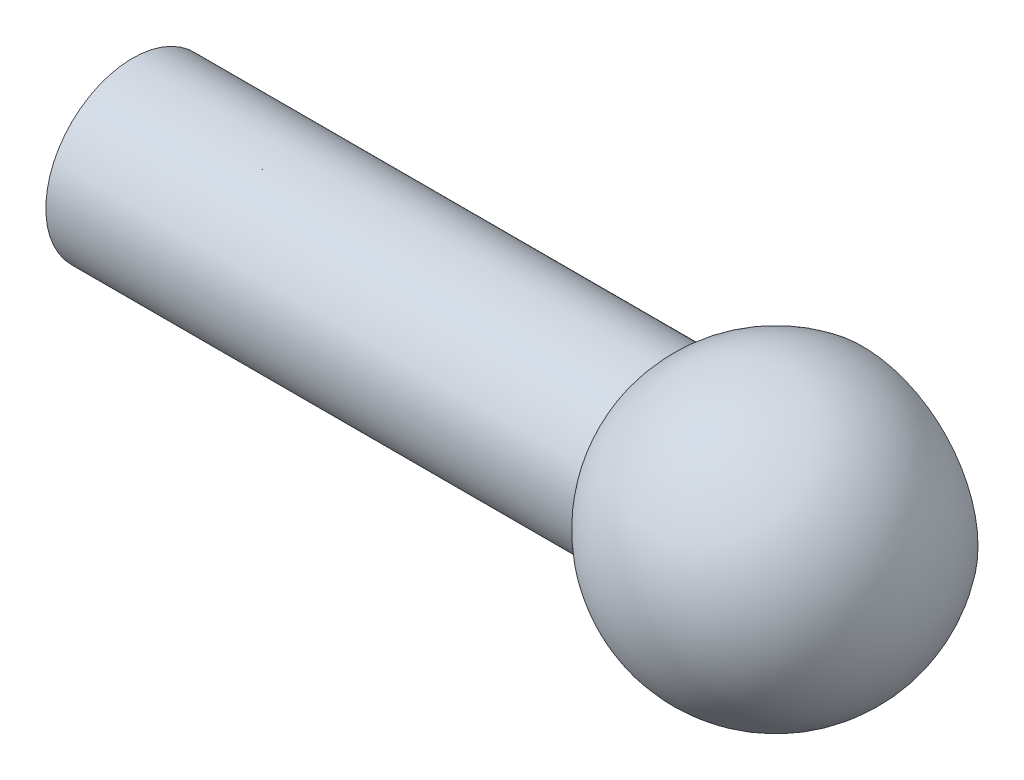
SolidWorks part; units mm, degrees
ref_plane "Piano frontale" through (0, 0, 0) normal (0, 0, 1) x (1, 0, 0)
ref_plane "Piano superiore" through (0, 0, 0) normal (0, 1, 0) x (1, 0, 0)
ref_plane "Piano destro" through (0, 0, 0) normal (1, 0, 0) x (0, 0, -1)
sketch "Schizzo2" plane through (0, 0, 0) normal (1, 0, 0) x (0, 0, -1)
  circle A0 centre (0, 0) radius 2.05
  dimension "D1" = 4.1
extrude "Estrusione-Estrusione1" add sketch "Schizzo2" along normal blind 13
sketch "Schizzo3" plane through (0, 0, 0) normal (-1, 0, 0) x (0, 0, 1)
  circle A0 centre (0, 0) radius 0.925
  dimension "D1" = 1.85
extrude "Taglio-Estrusione1" cut sketch "Schizzo3" against normal blind 12
sketch "Schizzo4" plane through (0, 0, 0) normal (0, 1, 0) x (1, 0, 0)
  line L1 (0, 2.05) -> (0, -2.05) construction
  line L2 (15.19, 3.41) -> (15.19, -3.41) construction
  line L3 (15.19, 3.41) -> (15.19, 1.975)
  line L4 (15.19, -1.975) -> (15.19, -3.41)
  arc A0 (15.19, -3.41) -> (15.19, 3.41) centre (15.19, 0) ccw
  arc A1 (15.19, -1.975) -> (15.19, 1.975) centre (15.19, 0) ccw
  point P4 (18.6, 0)
  dimension "D1" = 6.82
  dimension "D3" = 3.95
  dimension "D2" = 18.6
revolve "Rivoluzione1" add sketch "Schizzo4" angle 360 about L4
ref_plane "Piano1" through (0, 0, -2.05) normal (0, 0, -1) x (-1, 0, 0)
other "TaglioSuperficie1"
sketch "Schizzo5" plane through (0, 0, -2.05) normal (0, 0, -1) x (-1, 0, 0)
  circle A0 centre (-15.19, 0) radius 1.825
  dimension "D1" = 3.65
extrude "Taglio-Estrusione2" cut sketch "Schizzo5" against normal up to surface (2.05 mm away) up to plane "Piano frontale"
